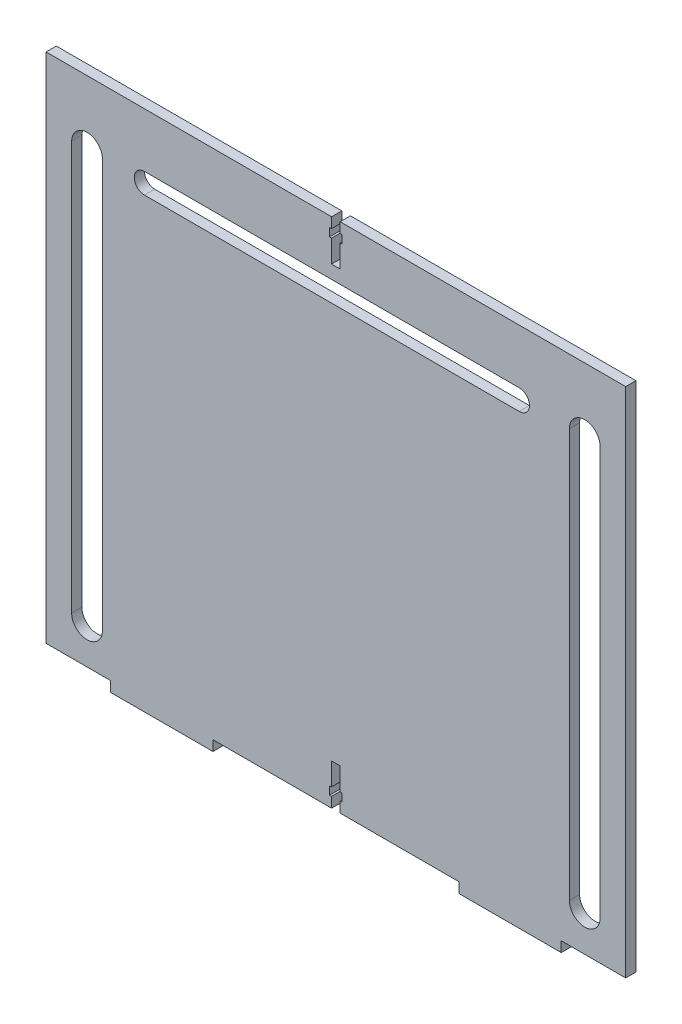
SolidWorks part; units mm, degrees
ref_plane "Plan de face" through (0, 0, 0) normal (0, 0, 1) x (1, 0, 0)
ref_plane "Plan de dessus" through (0, 0, 0) normal (0, 1, 0) x (1, 0, 0)
ref_plane "Plan de droite" through (0, 0, 0) normal (1, 0, 0) x (0, 0, -1)
sketch "Esquisse1" plane through (0, 0, 0) normal (0, 0, 1) x (1, 0, 0)
  line L0 (-51.3878, -19.0237) -> (-19.9178, -19.0237)
  line L1 (-19.9178, -19.0237) -> (-19.9178, -24.0237)
  line L2 (-19.9178, -24.0237) -> (30.0822, -24.0237)
  line L3 (30.0822, -24.0237) -> (30.0822, -19.0237)
  line L4 (30.0822, -19.0237) -> (87.9822, -19.0237)
  line L5 (-51.3878, -19.0237) -> (-51.3878, 230.9763)
  line L6 (87.9822, -19.0237) -> (87.9822, -14.0237)
  line L7 (87.9822, -14.0237) -> (86.9822, -14.0237)
  line L8 (86.9822, -14.0237) -> (86.9822, -10.0237)
  line L9 (86.9822, -10.0237) -> (87.9822, -10.0237)
  line L10 (87.9822, -10.0237) -> (87.9822, 0.9763)
  line L11 (87.9822, 0.9763) -> (92.1822, 0.9763)
  line L12 (-51.3878, 105.9763) -> (217.3578, 105.9763) construction
  line L13 (90.0822, 0.9763) -> (90.0822, 19.6102) construction
  line L14 (92.1822, -10.0237) -> (92.1822, 0.9763)
  line L15 (93.1822, -10.0237) -> (92.1822, -10.0237)
  line L16 (92.1822, -14.0237) -> (93.1822, -14.0237)
  line L17 (93.1822, -14.0237) -> (93.1822, -10.0237)
  line L18 (92.1822, -19.0237) -> (92.1822, -14.0237)
  line L19 (200.0822, -19.0237) -> (200.0822, -24.0237)
  line L20 (150.0822, -24.0237) -> (150.0822, -19.0237)
  line L21 (150.0822, -19.0237) -> (92.1822, -19.0237)
  line L22 (200.0822, -24.0237) -> (150.0822, -24.0237)
  line L23 (231.5522, -19.0237) -> (200.0822, -19.0237)
  line L24 (231.5522, -19.0237) -> (231.5522, 230.9763)
  line L25 (90.0822, 210.9763) -> (90.0822, 192.3425) construction
  line L26 (231.5522, 230.9763) -> (200.0822, 230.9763)
  line L28 (150.0822, 230.9763) -> (92.1822, 230.9763)
  line L31 (92.1822, 230.9763) -> (92.1822, 225.9763)
  line L32 (93.1822, 225.9763) -> (93.1822, 221.9763)
  line L33 (92.1822, 225.9763) -> (93.1822, 225.9763)
  line L34 (93.1822, 221.9763) -> (92.1822, 221.9763)
  line L35 (92.1822, 221.9763) -> (92.1822, 210.9763)
  line L36 (87.9822, 210.9763) -> (92.1822, 210.9763)
  line L37 (87.9822, 221.9763) -> (87.9822, 210.9763)
  line L38 (86.9822, 221.9763) -> (87.9822, 221.9763)
  line L39 (86.9822, 225.9763) -> (86.9822, 221.9763)
  line L40 (87.9822, 225.9763) -> (86.9822, 225.9763)
  line L41 (87.9822, 230.9763) -> (87.9822, 225.9763)
  line L42 (30.0822, 230.9763) -> (87.9822, 230.9763)
  line L46 (-51.3878, 230.9763) -> (-19.9178, 230.9763)
  line L47 (200.0822, 230.9763) -> (150.0822, 230.9763)
  line L48 (-19.9178, 230.9763) -> (30.0822, 230.9763)
  point P28 (231.5522, 105.9763)
  dimension "D2" = 31.47
  dimension "D3" = 5
  dimension "D4" = 50
  dimension "D5" = 5
  dimension "D6" = 57.9
  dimension "D7" = 5
  dimension "D8" = 1
  dimension "D9" = 1
  dimension "D10" = 11
  dimension "D11" = 2.1
  dimension "D12" = 4
extrude "Boss.-Extru.1" add sketch "Esquisse1" along normal blind 5
sketch "Esquisse2" plane through (0, 0, 0) normal (0, 0, -1) x (-1, 0, 0)
  line L0 (-211.5522, 199.4788) -> (-211.5522, 0) construction
  line L1 (-204.0522, 199.4788) -> (-204.0522, 0)
  line L2 (-219.0522, 199.4788) -> (-219.0522, 0)
  line L3 (-179.5792, 199.4788) -> (3.3361, 199.4788) construction
  line L4 (-179.5792, 204.4788) -> (3.3361, 204.4788)
  line L5 (-179.5792, 194.4788) -> (3.3361, 194.4788)
  line L6 (31.3878, 199.4788) -> (31.3878, 0) construction
  line L7 (38.8878, 199.4788) -> (38.8878, 0)
  line L8 (23.8878, 199.4788) -> (23.8878, 0)
  line L9 (51.3878, 230.9763) -> (51.3878, -19.0237) construction
  line L11 (-231.5522, -19.0237) -> (-231.5522, 230.9763) construction
  arc A0 (-204.0522, 199.4788) -> (-219.0522, 199.4788) centre (-211.5522, 199.4788) ccw
  arc A1 (-219.0522, 0) -> (-204.0522, 0) centre (-211.5522, 0) ccw
  arc A2 (-179.5792, 204.4788) -> (-179.5792, 194.4788) centre (-179.5792, 199.4788) ccw
  arc A3 (3.3361, 194.4788) -> (3.3361, 204.4788) centre (3.3361, 199.4788) ccw
  arc A4 (38.8878, 199.4788) -> (23.8878, 199.4788) centre (31.3878, 199.4788) ccw
  arc A5 (23.8878, 0) -> (38.8878, 0) centre (31.3878, 0) ccw
  point P2 (-211.5522, 99.7394)
  point P9 (-88.1216, 199.4788)
  point P16 (31.3878, 99.7394)
  dimension "D1" = 10
  dimension "D2" = 15
  dimension "D3" = 15
  dimension "D4" = 20
  dimension "D5" = 20
extrude "Enlèv. mat.-Extru.1" cut sketch "Esquisse2" against normal through all
